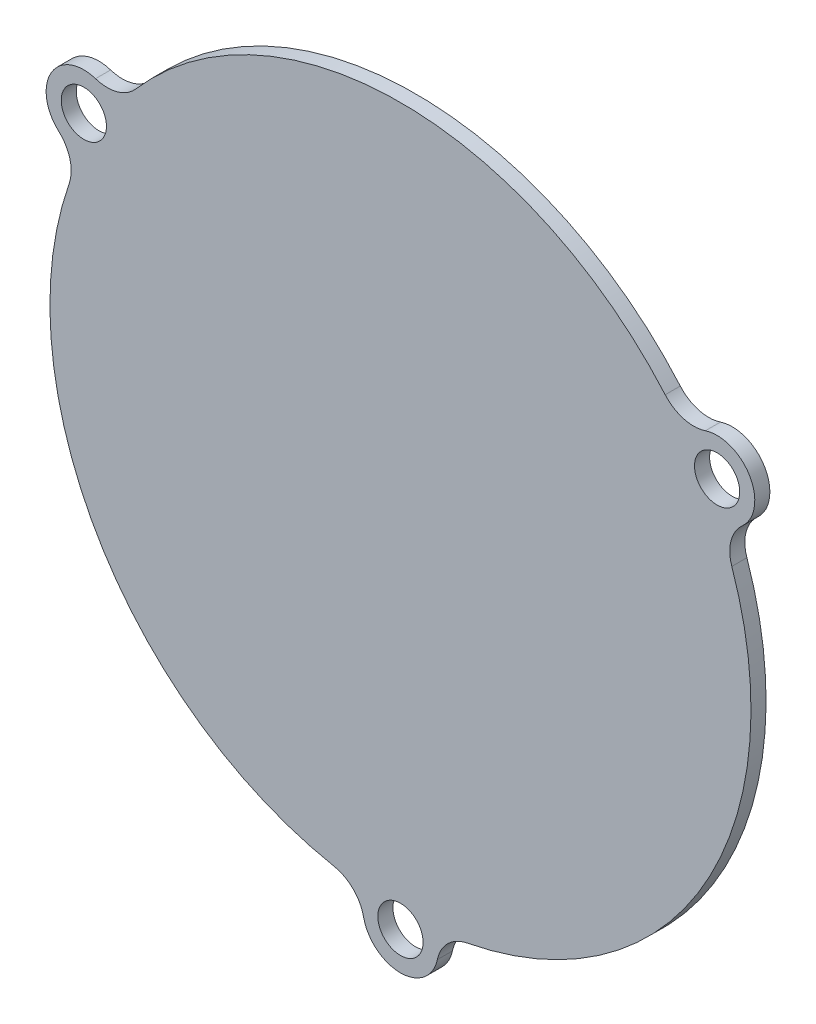
SolidWorks part; units mm, degrees
ref_plane "Plan1" through (0, 0, 0) normal (0, 0, 1) x (1, 0, 0)
ref_plane "Plan2" through (0, 0, 0) normal (0, 1, 0) x (1, 0, 0)
ref_plane "Plan3" through (0, 0, 0) normal (1, 0, 0) x (0, 0, -1)
sketch "Esquisse1" plane through (0, 0, 0) normal (0, 0, 1) x (1, 0, 0)
  line L0 (0, 0) -> (0, -108.1) construction
  arc A0 (17.6702, -91.3059) -> (87.9083, 30.3501) centre (0, 0) ccw
  arc A1 (-9.7851, -99.0619) -> (9.7851, -99.0619) centre (0, -97) ccw
  arc A2 (17.6702, -91.3059) -> (9.7851, -99.0619) centre (19.5703, -101.1237) ccw
  arc A3 (-9.7851, -99.0619) -> (-17.6702, -91.3059) centre (-19.5703, -101.1237) ccw
  arc A4 (-80.8975, 58.0051) -> (-70.2381, 60.9558) centre (-77.7906, 67.5102) ccw
  arc A5 (-80.8975, 58.0051) -> (-90.6826, 41.0568) centre (-84.0045, 48.5) ccw
  arc A6 (-87.9083, 30.3501) -> (-90.6826, 41.0568) centre (-97.3608, 33.6135) ccw
  arc A7 (90.6826, 41.0568) -> (87.9083, 30.3501) centre (97.3608, 33.6135) ccw
  arc A8 (90.6826, 41.0568) -> (80.8975, 58.0051) centre (84.0045, 48.5) ccw
  arc A9 (70.2381, 60.9558) -> (80.8975, 58.0051) centre (77.7906, 67.5102) ccw
  arc A10 (70.2381, 60.9558) -> (-70.2381, 60.9558) centre (0, 0) ccw
  arc A11 (-87.9083, 30.3501) -> (-17.6702, -91.3059) centre (0, 0) ccw
  circle A12 centre (0, -97) radius 6
  circle A13 centre (84.0045, 48.5) radius 6
  circle A14 centre (-84.0045, 48.5) radius 6
  dimension "D1" = 186
  dimension "D2" = 10
  dimension "D4" = 10
  dimension "D5" = 10
  dimension "D6" = 12
  dimension "D7" = 12
  dimension "D8" = 12
  dimension "D3" = 97
extrude "Base-Extrusion" add sketch "Esquisse1" along normal blind 4
